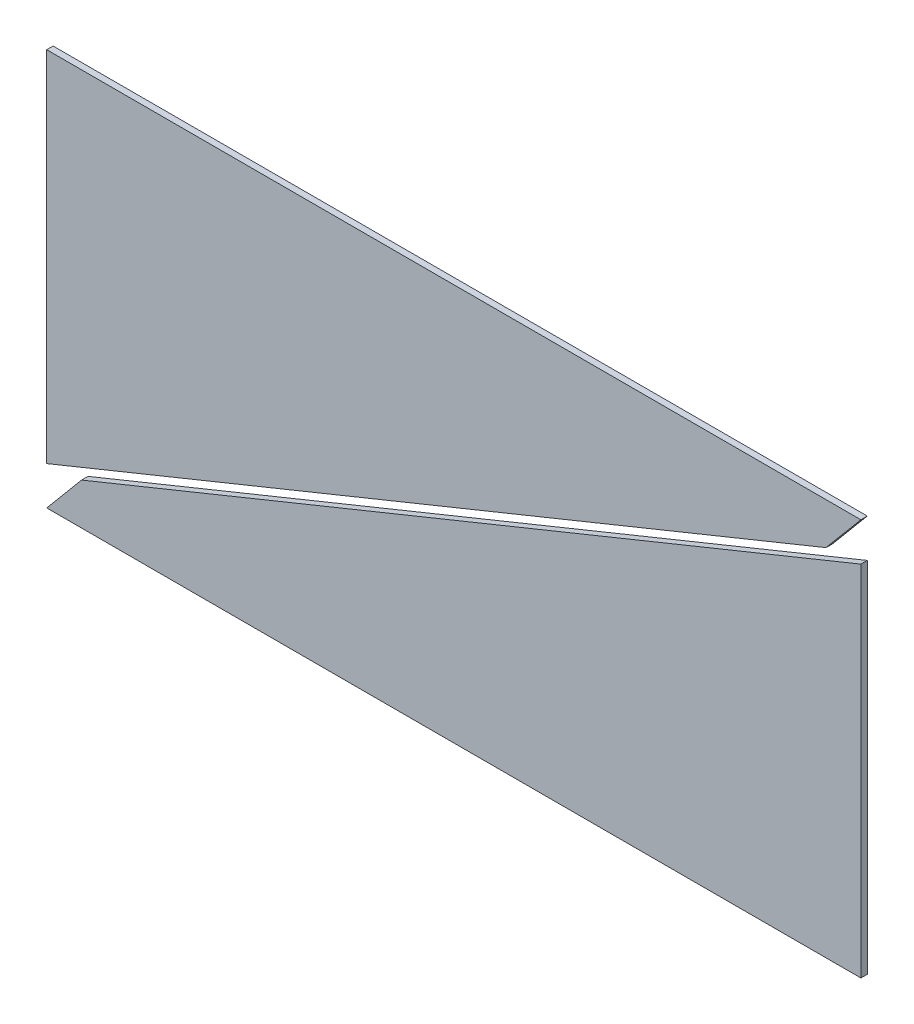
SolidWorks part; units mm, degrees
ref_plane "Front Plane" through (0, 0, 0) normal (0, 0, 1) x (1, 0, 0)
ref_plane "Top Plane" through (0, 0, 0) normal (0, 1, 0) x (1, 0, 0)
ref_plane "Right Plane" through (0, 0, 0) normal (1, 0, 0) x (0, 0, -1)
sketch "Sketch1" plane through (0, 0, 0) normal (0, 0, 1) x (1, 0, 0)
  line L1 (-15.9, -7.75) -> (15.9, -7.75)
  line L2 (-15.9, -7.75) -> (-15.9, 7.75)
  line L3 (-15.9, 7.75) -> (15.9, 7.75)
  line L4 (15.9, -7.75) -> (15.9, 7.75)
  line L5 (-15.9, -7.75) -> (15.9, 7.75) construction
  line L6 (-15.9, 7.75) -> (15.9, -7.75) construction
  point P0 (0, 0)
sketch "Sketch2" plane through (0, 0, 0) normal (0, 0, 1) x (1, 0, 0)
  line L0 (-15.9, -7.75) -> (-15.9, -6.25) construction
  line L1 (-15.9, -7.75) -> (-15.9, 7.75) construction
  line L4 (15.9, 7.75) -> (15.9, 6.25) construction
  line L5 (15.9, -7.75) -> (15.9, 7.75) construction
  line L6 (-15.9, -6.25) -> (-15.9, 7.75)
  line L7 (-15.9, 7.75) -> (15.9, 7.75)
  line L8 (15.9, 7.75) -> (14.5364, 6.125)
  line L9 (14.5364, 6.125) -> (-15.9, -6.25)
  line L10 (-15.9, -7.75) -> (15.9, -7.75)
  line L11 (15.9, -7.75) -> (15.9, 6.25)
  line L12 (-15.9, -7.75) -> (-14.5364, -6.125)
  line L13 (-14.5364, -6.125) -> (15.9, 6.25)
extrude "Boss-Extrude2" add sketch "Sketch2" along normal blind 0.25
